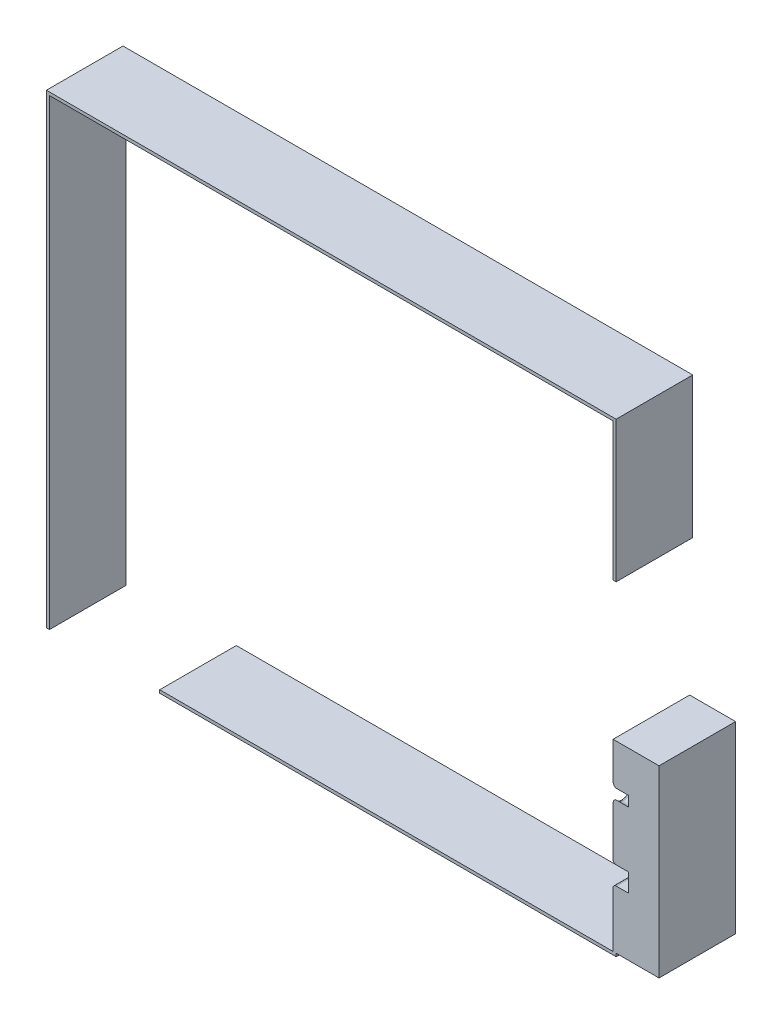
SolidWorks part; units mm, degrees
ref_plane "Front Plane" through (0, 0, 0) normal (0, 0, 1) x (1, 0, 0)
ref_plane "Top Plane" through (0, 0, 0) normal (0, 1, 0) x (1, 0, 0)
ref_plane "Right Plane" through (0, 0, 0) normal (1, 0, 0) x (0, 0, -1)
sketch "Sketch2" plane through (0, 0, 0) normal (0, 0, 1) x (1, 0, 0)
  line L1 (-1085.498, 700.9562) -> (774.502, 700.9562)
  line L2 (-1085.498, 700.9562) -> (-1085.498, -819.0438)
  line L3 (-1085.498, -819.0438) -> (774.502, -819.0438)
  line L4 (774.502, 700.9562) -> (774.502, -819.0438)
  dimension "D1" = 1520
  dimension "D2" = 1860
extrude "Boss-Extrude1" add sketch "Sketch2" along normal blind 260
sketch "Sketch3" plane through (0, 0, 0) normal (0, 0, -1) x (-1, 0, 0)
  line L0 (-774.502, 700.9562) -> (1085.498, 700.9562) construction
  line L1 (-764.502, 690.9562) -> (1075.498, 690.9562)
  line L2 (-764.502, 690.9562) -> (-764.502, -809.0438)
  line L3 (-764.502, -809.0438) -> (1075.498, -809.0438)
  line L4 (1075.498, 690.9562) -> (1075.498, -809.0438)
  dimension "D1" = 1500
  dimension "D2" = 1840
  dimension "D3" = 10
  dimension "D4" = 10
extrude "Cut-Extrude1" cut sketch "Sketch3" against normal blind 250
sketch "Sketch4" plane through (0, 0, 250) normal (0, 0, -1) x (-1, 0, 0)
  line L0 (-764.502, -209.0438) -> (1075.498, -209.0438)
  line L1 (155.498, 690.9562) -> (155.498, -809.0438)
  line L2 (-764.502, -809.0438) -> (1075.498, -809.0438) construction
  dimension "D1" = 1840
  dimension "D2" = 1500
  dimension "D3" = 920
  dimension "D4" = 600
  dimension "D5" = 0
  dimension "D6" = 0
sketch "Sketch5" plane through (774.502, 0, 0) normal (1, 0, 0) x (0, 0, -1)
  line L0 (-250, 690.9562) -> (-250, -809.0438) construction
  line L1 (-250, -809.0438) -> (0, -809.0438)
  line L2 (-250, -809.0438) -> (-250, -209.0438)
  line L3 (-250, -209.0438) -> (0, -209.0438)
  line L4 (0, -809.0438) -> (0, -209.0438)
  line L5 (-260, -819.0438) -> (0, -819.0438) construction
  dimension "D1" = 600
  dimension "D2" = 250
  dimension "D3" = 10
extrude "Boss-Extrude2" add sketch "Sketch5" along normal blind 140
sketch "Sketch6" plane through (764.502, 0, 0) normal (-1, 0, 0) x (0, 0, 1)
  line L0 (250, 690.9562) -> (250, -809.0438) construction
  line L1 (250, -375.6269) -> (250, -342.4607)
  circle A0 centre (225, -359.0438) radius 30
  line M3 (250, -809.0438) -> (250, 690.9562)
  dimension "D1" = 25
  dimension "D2" = 150
extrude "Cut-Extrude2" cut sketch "Sketch6" against normal blind 51 contours A0 M3
sketch "Sketch7" plane through (764.502, 0, 0) normal (-1, 0, 0) x (0, 0, 1)
  line L0 (250, -375.6269) -> (250, -809.0438) construction
  line L1 (190, -619.0438) -> (250, -619.0438)
  line L2 (190, -619.0438) -> (190, -559.0438)
  line L3 (190, -559.0438) -> (250, -559.0438)
  line L4 (250, -619.0438) -> (250, -559.0438)
  point P4 (250, -589.0438)
  dimension "D1" = 60
  dimension "D2" = 60
  dimension "D3" = 220
  dimension "D4" = 0
extrude "Cut-Extrude3" cut sketch "Sketch7" against normal blind 51
fillet "Fillet1" radius 10 4 edges at (764.502, -559.0438, 220) (764.502, -589.0438, 190) (764.502, -619.0438, 220) (764.502, -359.0438, 195)
sketch "Sketch8" plane through (0, -819.0438, 0) normal (0, -1, 0) x (1, 0, 0)
  line L0 (764.502, 250) -> (-1075.498, 250) construction
  line L1 (-1075.498, 250) -> (-715.498, 250)
  line L2 (-1075.498, 250) -> (-1075.498, 0)
  line L3 (-1075.498, 0) -> (-715.498, 0)
  line L4 (-715.498, 250) -> (-715.498, 0)
  dimension "D1" = 250
  dimension "D2" = 360
extrude "Cut-Extrude4" cut sketch "Sketch8" against normal blind 10
sketch "Sketch9" plane through (774.502, 0, 0) normal (1, 0, 0) x (0, 0, -1)
  line L1 (-250, -209.0438) -> (0, -209.0438)
  line L2 (-250, -209.0438) -> (-250, 240.9562)
  line L3 (-250, 240.9562) -> (0, 240.9562)
  line L4 (0, -209.0438) -> (0, 240.9562)
  dimension "D1" = 250
  dimension "D2" = 450
extrude "Cut-Extrude5" cut sketch "Sketch9" against normal blind 10
sketch "Sketch10" plane through (0, 0, 260) normal (0, 0, 1) x (1, 0, 0)
  line L1 (-1085.498, 700.9562) -> (774.502, 700.9562)
  line L2 (-1085.498, 700.9562) -> (-1085.498, -819.0438)
  line L3 (-1085.498, -819.0438) -> (774.502, -819.0438)
  line L4 (774.502, 700.9562) -> (774.502, -819.0438)
extrude "Cut-Extrude6" cut sketch "Sketch10" against normal blind 10
